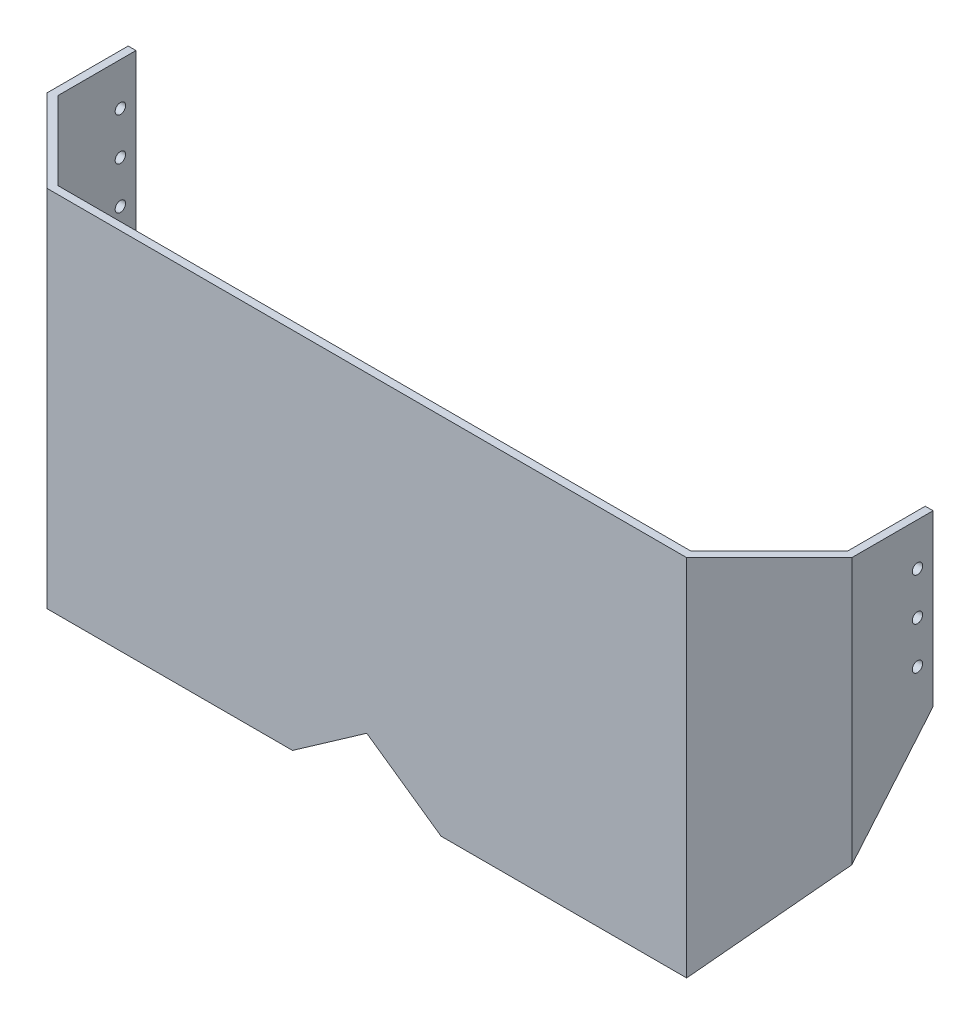
SolidWorks part; units mm, degrees
ref_plane "Front Plane" through (0, 0, 0) normal (0, 0, 1) x (1, 0, 0)
ref_plane "Top Plane" through (0, 0, 0) normal (0, 1, 0) x (1, 0, 0)
ref_plane "Right Plane" through (0, 0, 0) normal (1, 0, 0) x (0, 0, -1)
sketch "Sketch1" plane through (0, 0, 0) normal (0, 1, 0) x (1, 0, 0)
  line L0 (-61.5, 0) -> (61.5, 0)
  line L1 (-60.8787, 1.5) -> (60.8787, 1.5)
  line L2 (60.8787, 1.5) -> (75.8787, 16.5)
  line L3 (75.8787, 16.5) -> (75.8787, 31.5)
  line L4 (75.8787, 31.5) -> (77.3787, 31.5)
  line L5 (77.3787, 31.5) -> (77.3787, 15.8787)
  line L6 (77.3787, 15.8787) -> (61.5, 0)
  line L7 (-60.8787, 1.5) -> (-75.8787, 16.5)
  line L8 (-75.8787, 16.5) -> (-75.8787, 31.5)
  line L9 (-75.8787, 31.5) -> (-77.3787, 31.5)
  line L10 (-77.3787, 31.5) -> (-77.3787, 15.8787)
  line L11 (-77.3787, 15.8787) -> (-61.5, 0)
  point P2 (0, 0)
  dimension "D1" = 1.5
  dimension "D2" = 135
  dimension "D3" = 135
  dimension "D4" = 15
  dimension "D5" = 1.5
  dimension "D6" = 123
  dimension "D7" = 30
  dimension "D8" = 1.5
extrude "Boss-Extrude1" add sketch "Sketch1" along normal mid plane 70
sketch "Sketch2" plane through (0, 0, 0) normal (0, 0, 1) x (1, 0, 0)
  line L0 (0, -25) -> (-14.2815, -35)
  line L1 (-61.5, -35) -> (61.5, -35) construction
  line L2 (-14.2815, -35) -> (14.2815, -35)
  line L3 (14.2815, -35) -> (0, -25)
  point P4 (0, -35)
  dimension "D1" = 10
  dimension "D2" = 35
extrude "Cut-Extrude1" cut sketch "Sketch2" against normal up to surface (1.5 mm away) up to face at (0, 0, -1.5)
sketch "Sketch7" plane through (30.75, 0, 30.75) normal (0.7071, 0, 0.7071) x (0.7071, 0, -0.7071)
  line L0 (43.4871, -35) -> (65.9429, -16.1573)
  line L1 (65.9429, 35) -> (65.9429, -35) construction
  line L2 (43.4871, -35) -> (65.9429, -35) construction
  line L3 (43.4871, -35) -> (65.9429, -35)
  line L4 (65.9429, -35) -> (65.9429, -16.1573)
  dimension "D1" = 40
sketch "Sketch12" plane through (29.6893, 0, 29.6893) normal (-0.7071, 0, -0.7071) x (-0.7071, 0, 0.7071)
  line L1 (-44.1084, 35) -> (-44.1084, -35) construction
  line L6 (-44.1084, -35) -> (-65.3216, -17.2)
  line L7 (-43.4871, -35) -> (-65.9429, -35) construction
  line L8 (-65.3216, 35) -> (-65.3216, -35) construction
  line L9 (-65.3216, -17.2) -> (-65.3216, -35)
  line L10 (-65.3216, -35) -> (-44.1084, -35)
  dimension "D1" = 40
loft "Cut-Loft1" cut profiles "Sketch12", "Sketch7"
sketch "Sketch8" plane through (77.3787, 0, 0) normal (1, 0, 0) x (0, 0, -1)
  line L0 (15.8787, -16.1573) -> (31.5, 2.38)
  line L1 (31.5, 35) -> (31.5, -35) construction
  line L2 (0, -35) -> (15.8787, -16.1573) construction
  line L3 (15.8787, -16.1573) -> (15.8787, -35)
  line L4 (15.8787, -35) -> (31.5, -35)
  line L5 (31.5, -35) -> (31.5, 2.38)
sketch "Sketch13" plane through (75.8787, 0, 0) normal (-1, 0, 0) x (0, 0, 1)
  line L0 (-31.5, 0.6) -> (-31.5, -35)
  line L1 (-31.5, -35) -> (-31.5, 2.38) construction
  line L2 (-31.5, -35) -> (-16.5, -35)
  line L3 (-16.5, -35) -> (-16.5, -17.2)
  line L4 (-16.5, -17.2) -> (-31.5, 0.6)
  line L5 (-1.5, -35) -> (-16.5, -17.2) construction
  line L6 (-15.8787, -16.1573) -> (-31.5, 2.38) construction
loft "Cut-Loft2" cut profiles "Sketch8", "Sketch13"
mirror "Mirror1" about plane through (0, 0, 0) normal (1, 0, 0) of "Cut-Loft2", "Cut-Loft1"
sketch "Sketch14" plane through (0, 0, 0) normal (1, 0, 0) x (0, 0, -1)
  line L0 (31.5, 35) -> (28.5, 35) construction
  line L1 (15.8787, 35) -> (31.5, 35) construction
  line L2 (28.5, 35) -> (28.5, 26.845) construction
  line L3 (28.5, 26.845) -> (28.5, 18.69) construction
  line L4 (28.5, 18.69) -> (28.5, 10.535) construction
  line L7 (28.5, 10.535) -> (28.5, 2.38) construction
  circle A0 centre (28.5, 26.845) radius 1
  circle A1 centre (28.5, 18.69) radius 1
  circle A2 centre (28.5, 10.535) radius 1
  dimension "D1" = 2
  dimension "D2" = 2
  dimension "D3" = 3
extrude "Cut-Extrude7" cut sketch "Sketch14" against normal through all both and the other way through all
